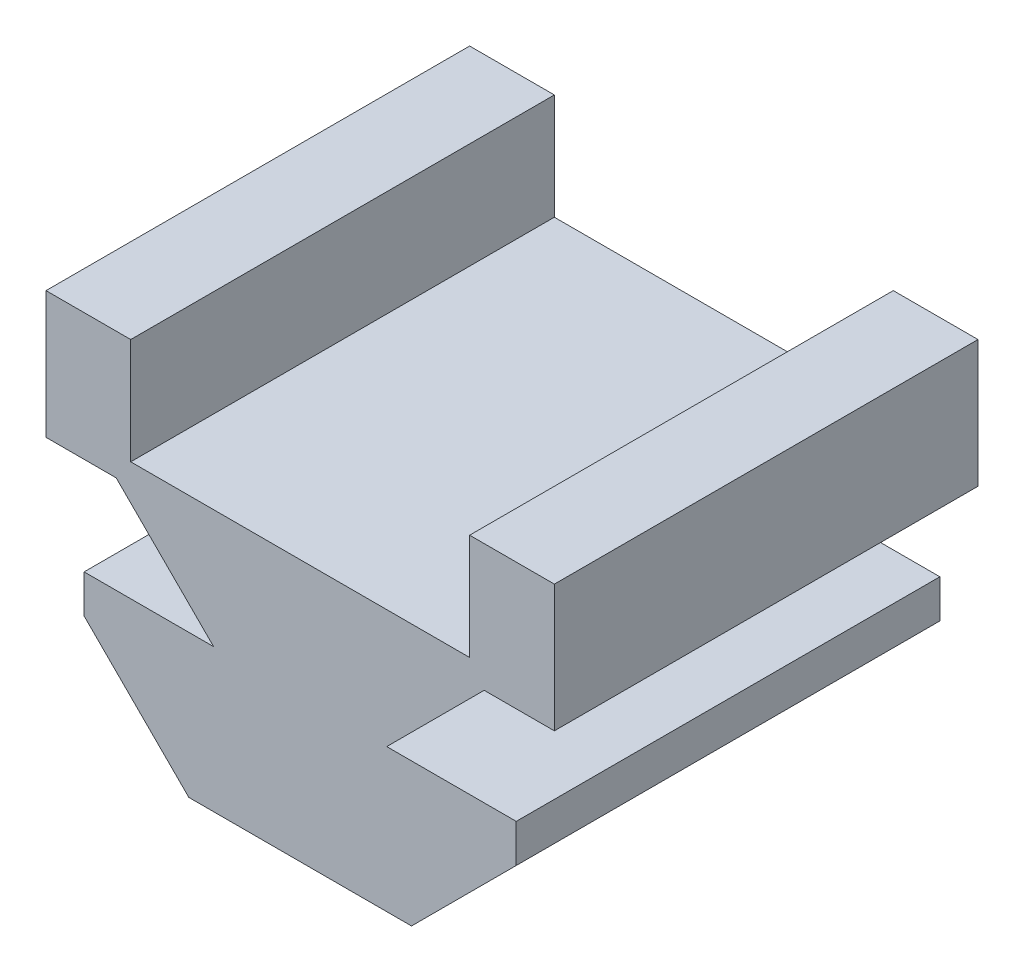
SolidWorks part; units mm, degrees
ref_plane "Alzado" through (0, 0, 0) normal (0, 0, 1) x (1, 0, 0)
ref_plane "Planta" through (0, 0, 0) normal (0, 1, 0) x (1, 0, 0)
ref_plane "Vista lateral" through (0, 0, 0) normal (1, 0, 0) x (0, 0, -1)
sketch "Croquis1" plane through (0, 0, 0) normal (0, 0, 1) x (1, 0, 0)
  line L0 (12.6279, -5.675) -> (15.1, -3.2029)
  line L8 (7.1649, -6.175) -> (10, -6.175)
  line L9 (15.1, -2.3) -> (15.1, -3.2029)
  line L10 (15.1, -2.3) -> (12.0429, -2.3)
  line L12 (7.3721, -5.675) -> (12.6279, -5.675)
  line L13 (10, -6.175) -> (10, 0.5) construction
  line L33 (7.3721, -5.675) -> (4.9, -3.2029)
  line L34 (4.9, -2.3) -> (4.9, -3.2029)
  line L35 (4.9, -2.3) -> (7.9571, -2.3)
  line L41 (12.0429, -2.3) -> (14.3429, 0)
  line L42 (7.9571, -2.3) -> (5.6571, 0)
  line L43 (14.3429, 0) -> (16, 0)
  line L49 (16, 0) -> (16, 3)
  line L50 (14, 3) -> (16, 3)
  line L51 (10, 0.5) -> (10, -6.175)
  line L54 (6, 0.5) -> (14, 0.5)
  line L56 (14, 0.5) -> (14, 3)
  line L62 (5.6571, 0) -> (4, 0)
  line L65 (7.1649, -6.175) -> (4.4, -3.4101)
  line L66 (4.4, -1.8) -> (4.4, -3.4101)
  line L67 (4.4, -1.8) -> (6.75, -1.8)
  line L68 (6.75, -1.8) -> (4.95, 0)
  line L69 (0, 0) -> (4.4, 0)
  line L70 (4.4, 0) -> (4.95, 0)
  line L75 (6, 0.5) -> (6, 3)
  line L76 (6, 3) -> (4, 3)
  line L77 (4, 0) -> (4, 3)
  line L89 (10, 0.5) -> (6, 0.5)
  point P0 (11.923, 0.7456)
  point P3 (10, -5.675)
  dimension "D1" = 10
  dimension "D2" = 4
  dimension "D5" = 2
  dimension "D4" = 3
  dimension "D6" = 0.5
extrude "Saliente-Extruir1" add sketch "Croquis1" along normal blind 10 contours L77 L62 L42 L35 L34 L33 L12 L51 L54 L75 L76 | L56 L54 L51 L12 L0 L9 L10 L41 L43 L49 L50
